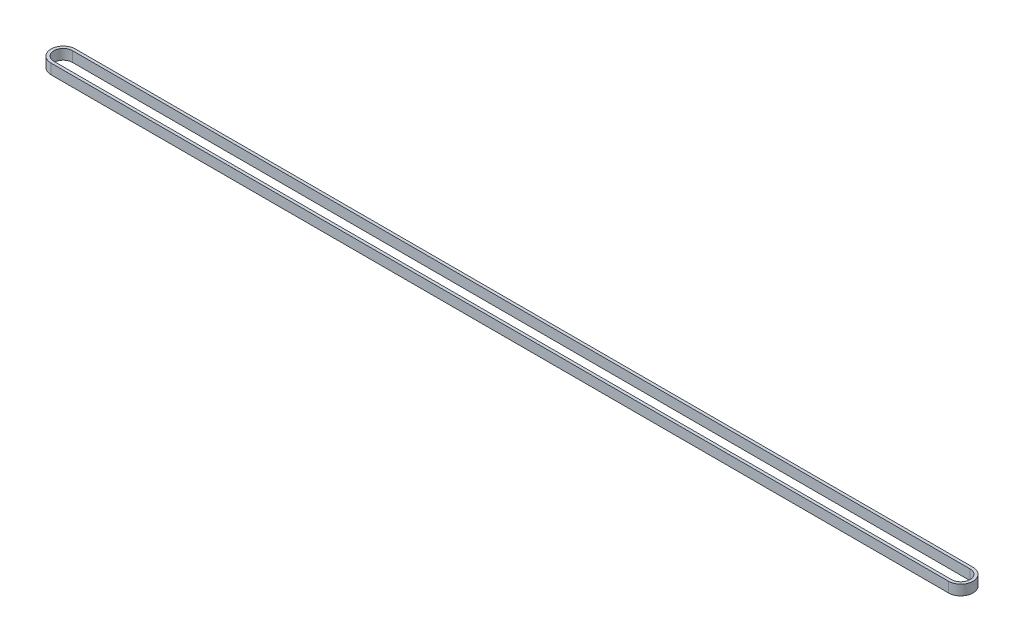
SolidWorks part; units mm, degrees
ref_plane "Front Plane" through (0, 0, 0) normal (0, 0, 1) x (1, 0, 0)
ref_plane "Top Plane" through (0, 0, 0) normal (0, 1, 0) x (1, 0, 0)
ref_plane "Right Plane" through (0, 0, 0) normal (1, 0, 0) x (0, 0, -1)
sketch "Sketch1" plane through (0, 0, 0) normal (0, 1, 0) x (1, 0, 0)
  line L0 (0, 8.37) -> (616.37, 8.37)
  line L1 (0, 6.37) -> (616.37, 6.37)
  line L2 (0, -6.37) -> (616.37, -6.37)
  line L3 (0, -8.37) -> (616.37, -8.37)
  arc A0 (0, 6.37) -> (0, -6.37) centre (0, 0) ccw
  arc A1 (616.37, -6.37) -> (616.37, 6.37) centre (616.37, 0) ccw
  arc A2 (616.37, -8.37) -> (616.37, 8.37) centre (616.37, 0) ccw
  arc A3 (0, 8.37) -> (0, -8.37) centre (0, 0) ccw
  dimension "D2" = 12.74
  dimension "D3" = 12.74
  dimension "D1" = 616.37
  dimension "D4" = 2
extrude "Boss-Extrude1" add sketch "Sketch1" along normal blind 7
